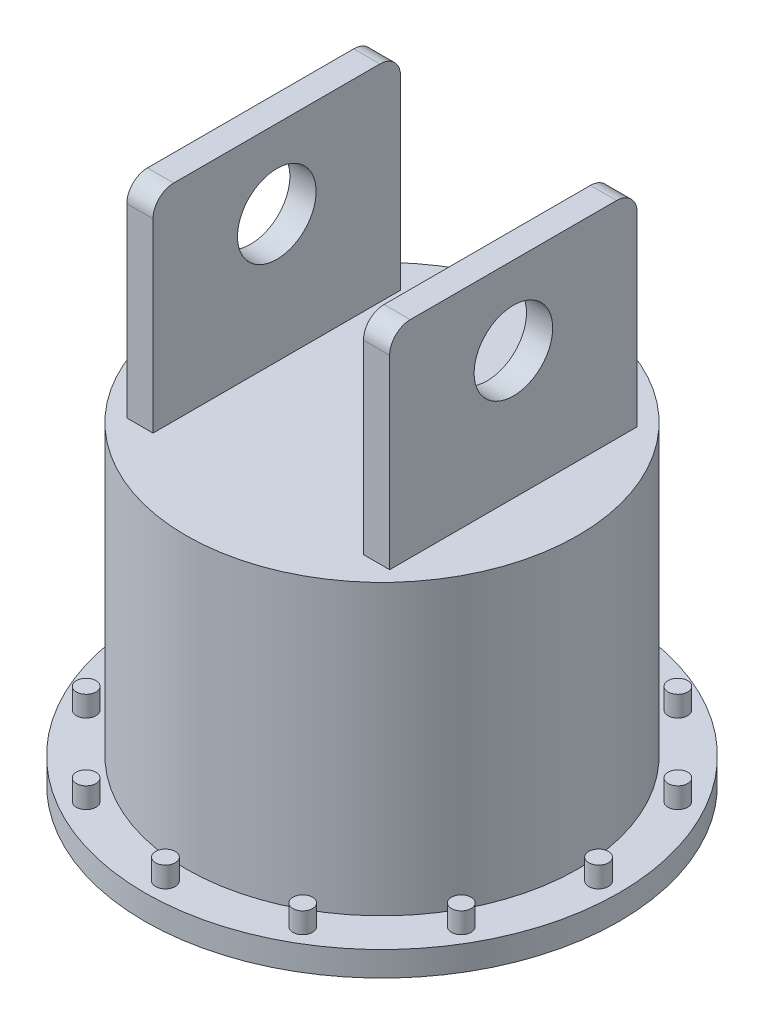
SolidWorks part; units mm, degrees
ref_plane "Alzado" through (0, 0, 0) normal (0, 0, 1) x (1, 0, 0)
ref_plane "Planta" through (0, 0, 0) normal (0, 1, 0) x (1, 0, 0)
ref_plane "Vista lateral" through (0, 0, 0) normal (1, 0, 0) x (0, 0, -1)
sketch "Croquis1" plane through (0, 0, 0) normal (0, 1, 0) x (1, 0, 0)
  circle A0 centre (0, 0) radius 115
  dimension "D1" = 230
extrude "Saliente-Extruir1" add sketch "Croquis1" along normal blind 12
sketch "Croquis2" plane through (0, 12, 0) normal (0, 1, 0) x (1, 0, 0)
  circle A0 centre (0, 0) radius 95
  dimension "D1" = 190
extrude "Saliente-Extruir2" add sketch "Croquis2" along normal blind 140
sketch "Croquis3" plane through (0, 12, 0) normal (0, 1, 0) x (1, 0, 0)
  line L0 (0, 115) -> (0, 95) construction
  circle A0 centre (0, 0) radius 115 construction
  circle A1 centre (0, 0) radius 95 construction
  circle A2 centre (0, 105) radius 4.7625
  dimension "D1" = 9.525
extrude "Saliente-Extruir3" add sketch "Croquis3" along normal blind 10
pattern_circular "MatrizC1" count 12 every 30 about axis through (0, 0, 0) along (0, 1, 0) of "Saliente-Extruir3"
sketch "Croquis4" plane through (0, 152, 0) normal (0, 1, 0) x (1, 0, 0)
  line L0 (0, 95) -> (0, -95) construction
  line L1 (0, 0) -> (57.35, 0) construction
  line L2 (-63.7, 60) -> (-51, -60) construction
  line L3 (63.7, -60) -> (51, -60)
  line L4 (63.7, -60) -> (63.7, 60)
  line L5 (63.7, 60) -> (51, 60)
  line L6 (51, -60) -> (51, 60)
  line L7 (63.7, -60) -> (51, 60) construction
  line L8 (63.7, 60) -> (51, -60) construction
  line L9 (-63.7, -60) -> (-51, 60) construction
  line L10 (-51, -60) -> (-51, 60)
  line L11 (-63.7, 60) -> (-51, 60)
  line L12 (-63.7, -60) -> (-63.7, 60)
  line L13 (-63.7, -60) -> (-51, -60)
  circle A0 centre (0, 0) radius 95 construction
  circle A1 centre (0, 0) radius 95 construction
  dimension "D1" = 120
  dimension "D2" = 12.7
  dimension "D3" = 51
extrude "Saliente-Extruir4" add sketch "Croquis4" along normal blind 100
sketch "Croquis5" plane through (-63.7, 0, 0) normal (-1, 0, 0) x (0, 0, 1)
  line L0 (0, 252) -> (0, 152) construction
  line L1 (-60, 252) -> (60, 252) construction
  line L2 (95, 152) -> (-95, 152) construction
  line L3 (60, 252) -> (-60, 252) construction
  circle A0 centre (0, 214) radius 19.05
  dimension "D1" = 38.1
  dimension "D2" = 38
extrude "Cortar-Extruir1" cut sketch "Croquis5" against normal up to surface (127.4 mm away) up to face at (63.7, 202, 0)
fillet "Redondeo1" radius 10 4 edges at (57.35, 252, -60) (57.35, 252, 60) (-57.35, 252, -60) (-57.35, 252, 60)
